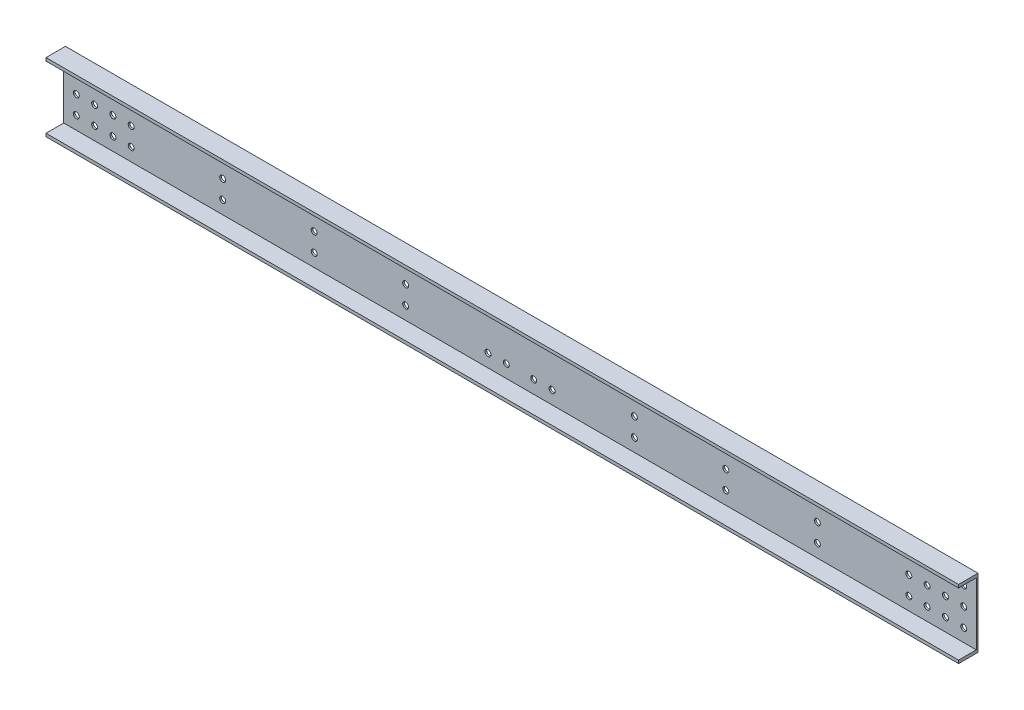
SolidWorks part; units mm, degrees
ref_plane "前视" through (0, 0, 0) normal (0, 0, 1) x (1, 0, 0)
ref_plane "上视" through (0, 0, 0) normal (0, 1, 0) x (1, 0, 0)
ref_plane "右视" through (0, 0, 0) normal (1, 0, 0) x (0, 0, -1)
sketch "草图1" plane through (0, 0, 0) normal (0, 0, 1) x (1, 0, 0)
  line L0 (-253.2778, 0) -> (2143.7198, 0) construction
  line L1 (0, 293.7967) -> (0, -293.7967) construction
  line L2 (1484.3386, 80) -> (1995, 80) construction
  line L3 (-1995, 150) -> (1995, 150)
  line L4 (-1995, 150) -> (-1995, -150)
  line L5 (-1995, -150) -> (1995, -150)
  line L6 (1995, 150) -> (1995, -150)
  line L7 (1940, 137.9179) -> (1940, -34.3032) construction
  line L8 (1860, 137.9179) -> (1860, -34.3032) construction
  line L9 (1780, -27.7215) -> (1780, 137.9179) construction
  line L10 (1700, 137.9179) -> (1700, -27.7215) construction
  line L11 (24.2318, 80) -> (382.2761, 80) construction
  line L12 (60, 137.9179) -> (60, -34.3032) construction
  line L13 (140, -34.3032) -> (140, 137.9179) construction
  circle A0 centre (1940, 0) radius 13
  circle A1 centre (1860, 0) radius 13
  circle A2 centre (1780, 0) radius 13
  circle A3 centre (1700, 0) radius 13
  circle A4 centre (1700, 80) radius 13
  circle A5 centre (1780, 80) radius 13
  circle A6 centre (1860, 80) radius 13
  circle A7 centre (1940, 80) radius 13
  circle A8 centre (1940, -80) radius 13
  circle A9 centre (1860, -80) radius 13
  circle A10 centre (1780, -80) radius 13
  circle A11 centre (1700, -80) radius 13
  circle A12 centre (-1700, -80) radius 13
  circle A13 centre (-1780, -80) radius 13
  circle A14 centre (-1860, -80) radius 13
  circle A15 centre (-1940, -80) radius 13
  circle A16 centre (-1940, 80) radius 13
  circle A17 centre (-1860, 80) radius 13
  circle A18 centre (-1780, 80) radius 13
  circle A19 centre (-1700, 80) radius 13
  circle A20 centre (-1700, 0) radius 13
  circle A21 centre (-1780, 0) radius 13
  circle A22 centre (-1860, 0) radius 13
  circle A23 centre (-1940, 0) radius 13
  circle A24 centre (60, 80) radius 13
  circle A25 centre (140, 80) radius 13
  circle A28 centre (140, -80) radius 13
  circle A29 centre (60, -80) radius 13
  circle A30 centre (-60, -80) radius 13
  circle A31 centre (-140, -80) radius 13
  circle A34 centre (-140, 80) radius 13
  circle A35 centre (-60, 80) radius 13
  dimension "D8" = 26
  dimension "D11" = 26
  dimension "D1" = 300
  dimension "D2" = 3990
  dimension "D3" = 80
  dimension "D4" = 55
  dimension "D5" = 80
  dimension "D6" = 80
  dimension "D7" = 80
  dimension "D9" = 60
  dimension "D10" = 80
extrude "基体-拉伸" add sketch "草图1" along normal blind 7.5
sketch "草图2" plane through (0, 0, 7.5) normal (0, 0, 1) x (1, 0, 0)
  line L0 (1995, -150) -> (1995, 150) construction
  line L1 (-1995, 150) -> (1995, 150)
  line L2 (-1995, 150) -> (-1995, 136.5)
  line L3 (-1995, 136.5) -> (1995, 136.5)
  line L4 (1995, 150) -> (1995, 136.5)
  line L5 (-335.9089, 0) -> (412.8346, 0) construction
  line L6 (1995, -150) -> (1995, -136.5)
  line L7 (-1995, -136.5) -> (1995, -136.5)
  line L8 (-1995, -150) -> (-1995, -136.5)
  line L9 (-1995, -150) -> (1995, -150)
  dimension "D1" = 13.5
extrude "凸台-拉伸1" add sketch "草图2" along normal blind 77.5
sketch "草图3" plane through (0, 0, 0) normal (0, 0, -1) x (-1, 0, 0)
  line L0 (-2700, 80) -> (47300, 80) construction
  line L1 (-2700, 0) -> (47300, 0) construction
  line L2 (-2700, -80) -> (47300, -80) construction
  line L3 (-1300, -957.9157) -> (-1300, 49042.0843) construction
  circle A0 centre (-1700, 80) radius 13 construction
  circle A1 centre (-1300, 80) radius 13
  circle A2 centre (-1300, 0) radius 13
  circle A3 centre (-1300, -80) radius 13
  dimension "D5" = 400
  dimension "D1" = 26
extrude "切除-拉伸1" cut sketch "草图3" against normal through all
pattern_linear "阵列(线性)1" count 3 spacing 400 along (-1, 0, 0) of "切除-拉伸1"
pattern_linear "阵列(线性)2" count 2 spacing 1800 along (-1, 0, 0) of "切除-拉伸1", "阵列(线性)1"
